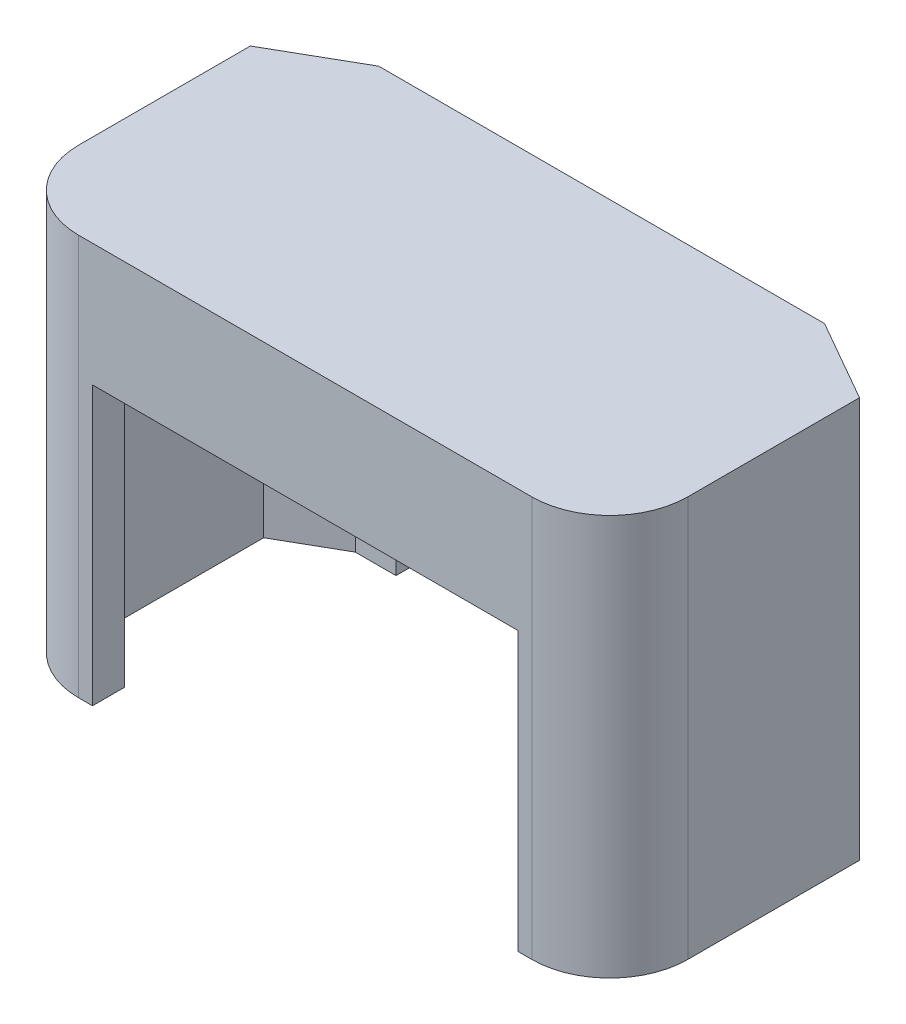
SolidWorks part; units mm, degrees
ref_plane "Front Plane" through (0, 0, 0) normal (0, 0, 1) x (1, 0, 0)
ref_plane "Top Plane" through (0, 0, 0) normal (0, 1, 0) x (1, 0, 0)
ref_plane "Right Plane" through (0, 0, 0) normal (1, 0, 0) x (0, 0, -1)
sketch "Sketch1" plane through (0, 0, 0) normal (0, 1, 0) x (1, 0, 0)
  line L0 (-38.45, 11.7) -> (-30.24, 16.4)
  line L1 (-31.95, -16.4) -> (31.95, -16.4)
  line L2 (-38.45, -9.9) -> (-38.45, 11.7)
  line L3 (-30.24, 16.4) -> (30.24, 16.4)
  line L4 (38.45, -9.9) -> (38.45, 11.7)
  line L5 (-38.45, -16.4) -> (38.45, 16.4) construction
  line L6 (-38.45, 16.4) -> (38.45, -16.4) construction
  line L7 (30.24, 16.4) -> (38.45, 11.7)
  line L8 (-42.95, -9.9) -> (-42.95, 14.3091)
  line L9 (-42.95, 14.3091) -> (-31.4369, 20.9)
  line L10 (-31.4369, 20.9) -> (31.4369, 20.9)
  line L11 (31.4369, 20.9) -> (42.95, 14.3091)
  line L12 (42.95, -9.9) -> (42.95, 14.3091)
  line L13 (-31.95, -20.9) -> (31.95, -20.9)
  arc A0 (31.95, -16.4) -> (38.45, -9.9) centre (31.95, -9.9) ccw
  arc A1 (-31.95, -16.4) -> (-38.45, -9.9) centre (-31.95, -9.9) cw
  arc A2 (31.95, -20.9) -> (42.95, -9.9) centre (31.95, -9.9) ccw
  arc A3 (-31.95, -20.9) -> (-42.95, -9.9) centre (-31.95, -9.9) cw
  point P0 (0, 0)
  dimension "D7" = 6.5
  dimension "D1" = 32.8
  dimension "D2" = 76.9
  dimension "D3" = 4.7
  dimension "D4" = 8.21
  dimension "D5" = 8.21
  dimension "D6" = 4.7
  dimension "D8" = 4.5
extrude "Boss-Extrude1" add sketch "Sketch1" along normal blind 52
sketch "Sketch2" plane through (0, 52, 0) normal (0, 1, 0) x (1, 0, 0)
  line L6 (-31.95, -20.9) -> (31.95, -20.9)
  line L7 (42.95, -9.9) -> (42.95, 14.3091)
  line L8 (42.95, 14.3091) -> (31.4369, 20.9)
  line L9 (31.4369, 20.9) -> (-31.4369, 20.9)
  line L10 (-31.4369, 20.9) -> (-42.95, 14.3091)
  line L11 (-42.95, 14.3091) -> (-42.95, -9.9)
  line L12 (-31.95, -20.9) -> (31.95, -20.9)
  line L13 (42.95, -9.9) -> (42.95, 14.3091)
  line L14 (42.95, 14.3091) -> (31.4369, 20.9)
  line L15 (31.4369, 20.9) -> (-31.4369, 20.9)
  line L16 (-31.4369, 20.9) -> (-42.95, 14.3091)
  line L17 (-42.95, 14.3091) -> (-42.95, -9.9)
  arc A2 (-42.95, -9.9) -> (-31.95, -20.9) centre (-31.95, -9.9) ccw
  arc A3 (31.95, -20.9) -> (42.95, -9.9) centre (31.95, -9.9) ccw
  arc A4 (-42.95, -9.9) -> (-31.95, -20.9) centre (-31.95, -9.9) ccw
  arc A5 (31.95, -20.9) -> (42.95, -9.9) centre (31.95, -9.9) ccw
  dimension "D1" = 0
extrude "Boss-Extrude2" add sketch "Sketch2" along normal blind 4.5
sketch "Sketch3" plane through (0, 0, 20.9) normal (0, 0, 1) x (1, 0, 0)
  line L0 (-31.95, 0) -> (31.95, 0) construction
  line L1 (-30, 39.2) -> (30, 39.2)
  line L2 (-30, 39.2) -> (-30, 0)
  line L3 (-30, 0) -> (30, 0)
  line L4 (30, 39.2) -> (30, 0)
  line L5 (-30, 39.2) -> (30, 0) construction
  line L6 (-30, 0) -> (30, 39.2) construction
  line L7 (-31.95, 52) -> (31.95, 52) construction
  point P0 (0, 19.6)
  point P5 (0, 0)
  dimension "D1" = 60
  dimension "D2" = 12.8
extrude "Cut-Extrude1" cut sketch "Sketch3" against normal up to next
sketch "Sketch4" plane through (0, 0, -20.9) normal (0, 0, -1) x (-1, 0, 0)
  line L0 (-31.4369, 0) -> (31.4369, 0) construction
  line L1 (-24.5, 12) -> (24.5, 12)
  line L2 (-24.5, 12) -> (-24.5, 0)
  line L3 (-24.5, 0) -> (24.5, 0)
  line L4 (24.5, 12) -> (24.5, 0)
  line L5 (-24.5, 12) -> (24.5, 0) construction
  line L6 (-24.5, 0) -> (24.5, 12) construction
  line L7 (-30.24, 52) -> (30.24, 52) construction
  point P0 (0, 6)
  point P7 (0, 0)
  dimension "D1" = 49
  dimension "D2" = 40
extrude "Cut-Extrude2" cut sketch "Sketch4" against normal up to next
sketch "Sketch5" plane through (0, 0, -20.9) normal (0, 0, -1) x (-1, 0, 0)
  line L0 (0, 12) -> (0, 56.5) construction
  line L1 (-38.475, -8.6) -> (-28.975, -8.6)
  line L2 (-38.475, -8.6) -> (-38.475, 19.9)
  line L3 (-38.475, 19.9) -> (-28.975, 19.9)
  line L4 (-28.975, -8.6) -> (-28.975, 19.9)
  line L5 (-38.475, -8.6) -> (-28.975, 19.9) construction
  line L6 (-38.475, 19.9) -> (-28.975, -8.6) construction
  line L7 (24.5, 12) -> (-24.5, 12) construction
  line L8 (-31.4369, 56.5) -> (31.4369, 56.5) construction
  line L9 (-42.95, 56.5) -> (-31.4369, 56.5) construction
  line L10 (-41.025, 19.9) -> (-26.425, 19.9)
  line L11 (-41.025, 19.9) -> (-41.025, 22.6)
  line L12 (-41.025, 22.6) -> (-26.425, 22.6)
  line L13 (-26.425, 19.9) -> (-26.425, 22.6)
  line L14 (-37.475, 22.6) -> (-29.975, 22.6)
  line L15 (-37.475, 22.6) -> (-37.475, 56.5)
  line L16 (-37.475, 56.5) -> (-29.975, 56.5)
  line L17 (-29.975, 22.6) -> (-29.975, 56.5)
  line L18 (-42.95, 0) -> (-24.5, 0) construction
  point P0 (-33.725, 5.65)
  point P19 (-33.725, 22.6)
  point P20 (-33.725, -8.6)
  point P21 (-33.725, 56.5)
  point P24 (-33.725, 0)
  dimension "D1" = 28.5
  dimension "D2" = 2.7
  dimension "D3" = 14.6
  dimension "D4" = 9.5
  dimension "D5" = 7.5
  dimension "D6" = 33.9
